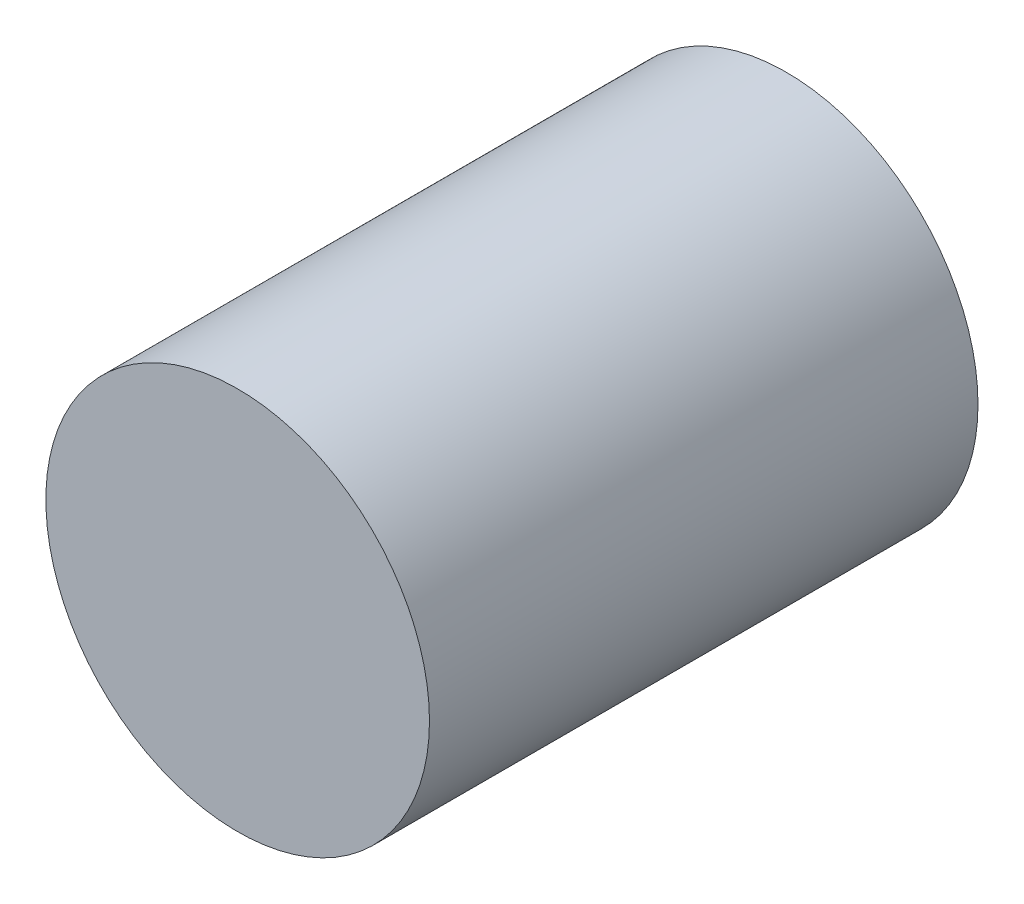
SolidWorks part; units mm, degrees
ref_plane "Front Plane" through (0, 0, 0) normal (0, 0, 1) x (1, 0, 0)
ref_plane "Top Plane" through (0, 0, 0) normal (0, 1, 0) x (1, 0, 0)
ref_plane "Right Plane" through (0, 0, 0) normal (1, 0, 0) x (0, 0, -1)
sketch "Sketch1" plane through (0, 0, 0) normal (0, 0, 1) x (1, 0, 0)
  line L0 (-64.4613, 54.2738) -> (-64.4613, -54.2738)
  line L1 (-62.4613, 52.2738) -> (62.4613, 52.2738)
  line L2 (-62.4613, 52.2738) -> (-62.4613, -52.2738)
  line L3 (-62.4613, -52.2738) -> (62.4613, -52.2738)
  line L4 (62.4613, 52.2738) -> (62.4613, -52.2738)
  line L5 (-62.4613, 52.2738) -> (62.4613, -52.2738) construction
  line L6 (-62.4613, -52.2738) -> (62.4613, 52.2738) construction
  line L7 (-64.4613, -54.2738) -> (64.4613, -54.2738)
  line L8 (64.4613, 54.2738) -> (64.4613, -54.2738)
  line L9 (-64.4613, 54.2738) -> (64.4613, 54.2738)
  point P0 (0, 0)
  dimension "D1" = 2
extrude "Boss-Extrude1" add sketch "Sketch1" along normal blind 50
sketch "Sketch2" plane through (0, 0, 0) normal (0, 0, 1) x (1, 0, 0)
  circle A0 centre (0, 0) radius 48.4966
extrude "Boss-Extrude2" add sketch "Sketch2" along normal up to surface (50 mm away) separate body up to face at (0, 0, 50)
sketch "Sketch3" plane through (0, 0, 0) normal (0, 0, 1) x (1, 0, 0)
  circle A0 centre (-51.1264, 41.5168) radius 6.9941
  circle A1 centre (46.4615, 43.756) radius 6.1207
extrude "Boss-Extrude3" add sketch "Sketch3" along normal blind 20 separate body
delete or keep bodies "Body-Delete1" type delete bodies bodies 104 101 102
